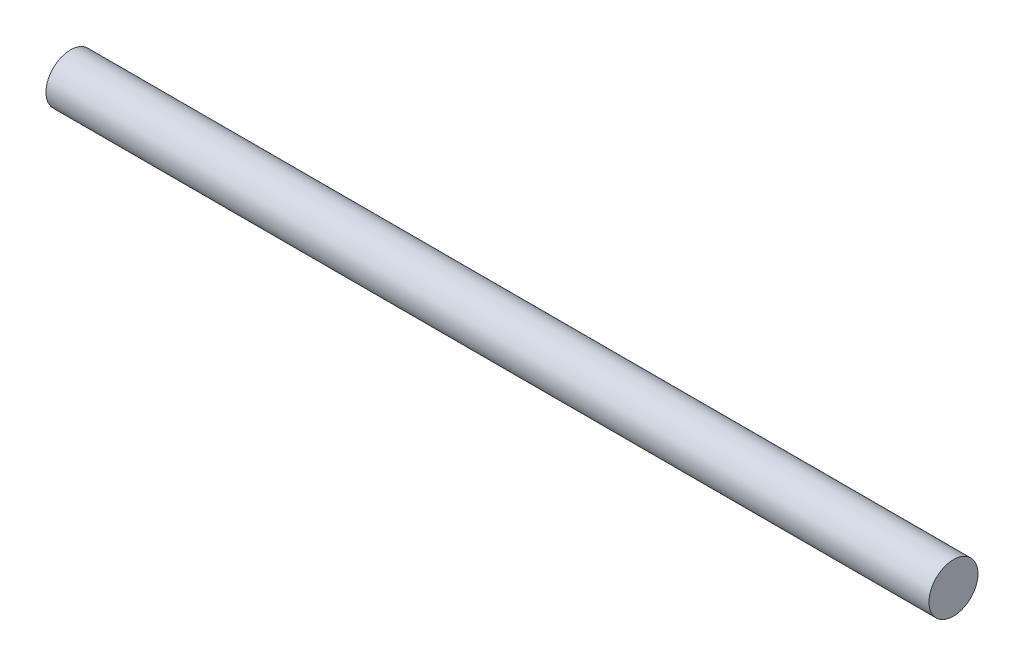
SolidWorks part; units mm, degrees
ref_plane "Front Plane" through (0, 0, 0) normal (0, 0, 1) x (1, 0, 0)
ref_plane "Top Plane" through (0, 0, 0) normal (0, 1, 0) x (1, 0, 0)
ref_plane "Right Plane" through (0, 0, 0) normal (1, 0, 0) x (0, 0, -1)
sketch "Sketch1" plane through (0, 0, 0) normal (1, 0, 0) x (0, 0, -1)
  circle A0 centre (0, 0) radius 2.5
  dimension "D1" = 5
extrude "Boss-Extrude1" add sketch "Sketch1" against normal blind 90
